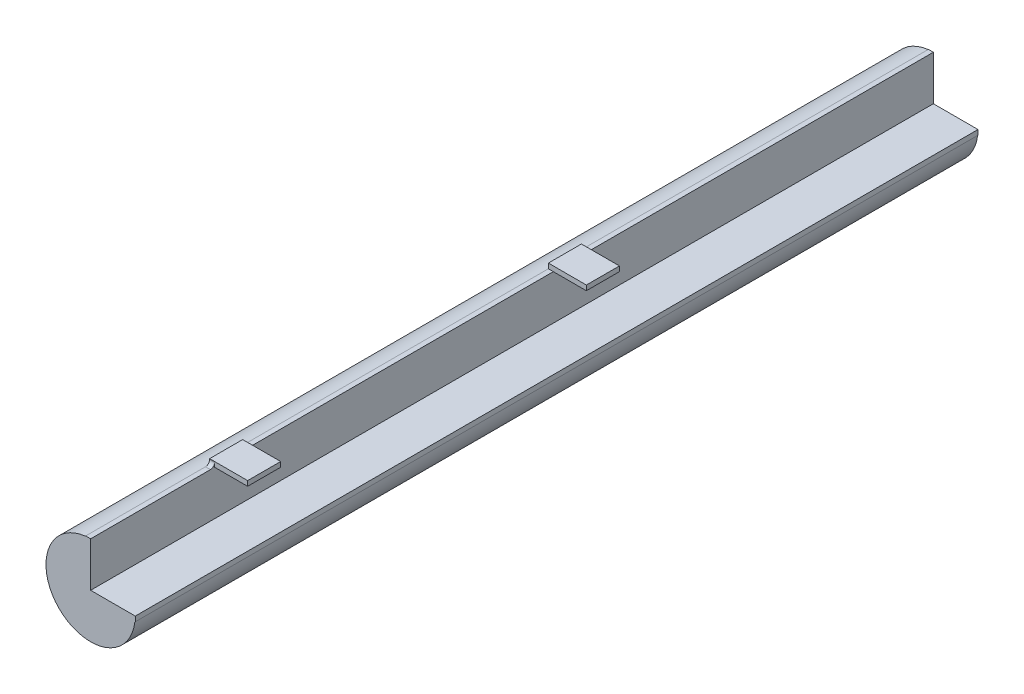
SolidWorks part; units mm, degrees
ref_plane "Front Plane" through (0, 0, 0) normal (0, 0, 1) x (1, 0, 0)
ref_plane "Top Plane" through (0, 0, 0) normal (0, 1, 0) x (1, 0, 0)
ref_plane "Right Plane" through (0, 0, 0) normal (1, 0, 0) x (0, 0, -1)
sketch "Sketch4" plane through (0, 0, 0) normal (0, 0, 1) x (1, 0, 0)
  line L0 (0, 0) -> (27, 0)
  line L5 (0, 27) -> (0, 0)
  line L6 (0, 27) -> (-3, 27)
  line L7 (-3, 27) -> (-3, 26.8328)
  line L8 (27, 0) -> (27, -3)
  line L9 (27, -3) -> (26.8001, -3)
  arc A1 (-3, 26.8328) -> (26.8001, -3) centre (-0.0331, -0.0037) ccw
  dimension "D3" = 27
  dimension "D1" = 27
  dimension "D2" = 27
  dimension "D4" = 3
  dimension "D5" = 3
  dimension "D6" = 0.1672
  dimension "D7" = 0.1999
extrude "Boss-Extrude1" add sketch "Sketch4" along normal mid plane 510
sketch "Sketch5" plane through (0, 27, 0) normal (0, 1, 0) x (1, 0, 0)
  line L0 (-3, -255) -> (-3, 255) construction
  line L1 (-3, -180) -> (20, -180)
  line L2 (-3, -180) -> (-3, -160)
  line L3 (-3, -160) -> (20, -160)
  line L4 (20, -180) -> (20, -160)
  line L5 (0, -255) -> (-3, -255) construction
  line L7 (-3, 45) -> (20, 45)
  line L8 (-3, 45) -> (-3, 25)
  line L9 (-3, 25) -> (20, 25)
  line L10 (20, 45) -> (20, 25)
  dimension "D1" = 20
  dimension "D2" = 23
  dimension "D3" = 75
  dimension "D4" = 20
  dimension "D5" = 23
  dimension "D6" = 280
extrude "Boss-Extrude2" add sketch "Sketch5" along normal blind 3
ref_plane "Plane1" through (-3, 27, 180) normal (1, 0, 0) x (0, 0, -1)
sketch "Sketch6" plane through (-3, 27, 180) normal (1, 0, 0) x (0, 0, -1)
  line L0 (0, 3) -> (0, 2.5)
  line L1 (-2.5, 0) -> (-3, 0)
  line L2 (-75, 0) -> (0, 0) construction
  line L3 (-3, 0) -> (0, 0)
  arc A0 (0, 2.5) -> (-2.5, 0) centre (-2.5, 2.5) cw
  spline S0 degree 1 poles (0, 3) (0, 0) knots 0 0 1 1
  dimension "D1" = 2.5
  dimension "D2" = 3
extrude "Boss-Extrude3" add sketch "Sketch6" along normal blind 3 contours S0 A0 L3
